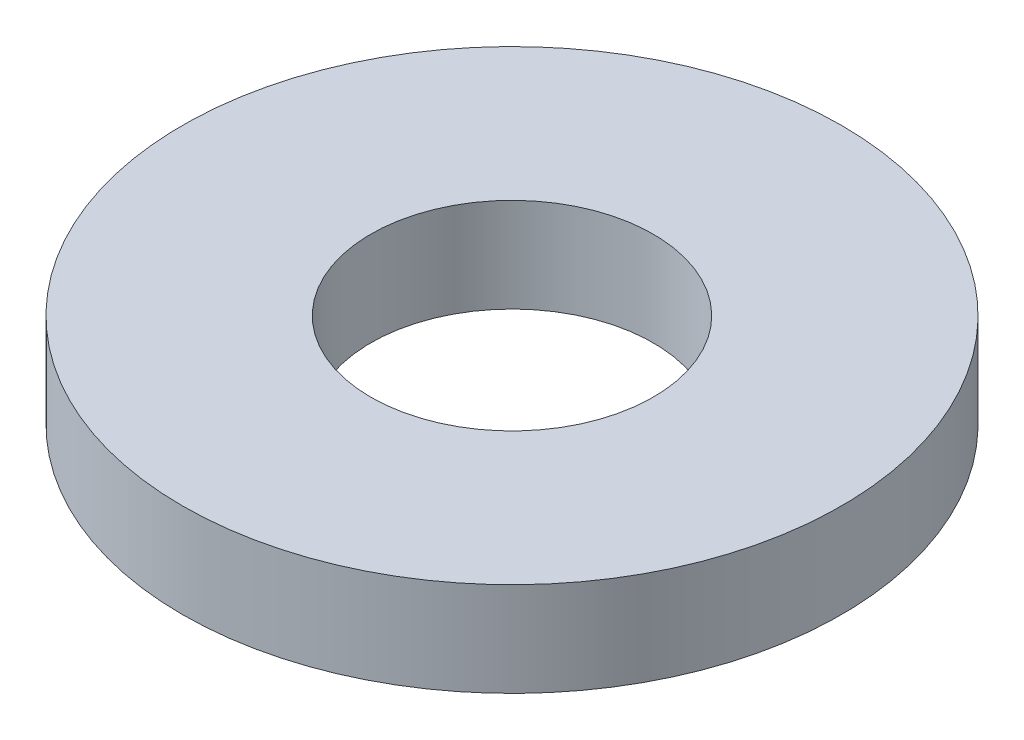
SolidWorks part; units mm, degrees
ref_plane "Alzado" through (0, 0, 0) normal (0, 0, 1) x (1, 0, 0)
ref_plane "Planta" through (0, 0, 0) normal (0, 1, 0) x (1, 0, 0)
ref_plane "Vista lateral" through (0, 0, 0) normal (1, 0, 0) x (0, 0, -1)
sketch "Croquis base" plane through (0, 0, 0) normal (0, 1, 0) x (1, 0, 0)
  circle A0 centre (0, 0) radius 3.5
  dimension "D1" = 7
extrude "Saliente-Extruir1" add sketch "Croquis base" along normal blind 1
sketch "Croquis barreno" plane through (0, 1, 0) normal (0, 1, 0) x (1, 0, 0)
  circle A0 centre (0, 0) radius 1.5
  dimension "D1" = 3
extrude "Cortar-Extruir1" cut sketch "Croquis barreno" against normal blind 1
